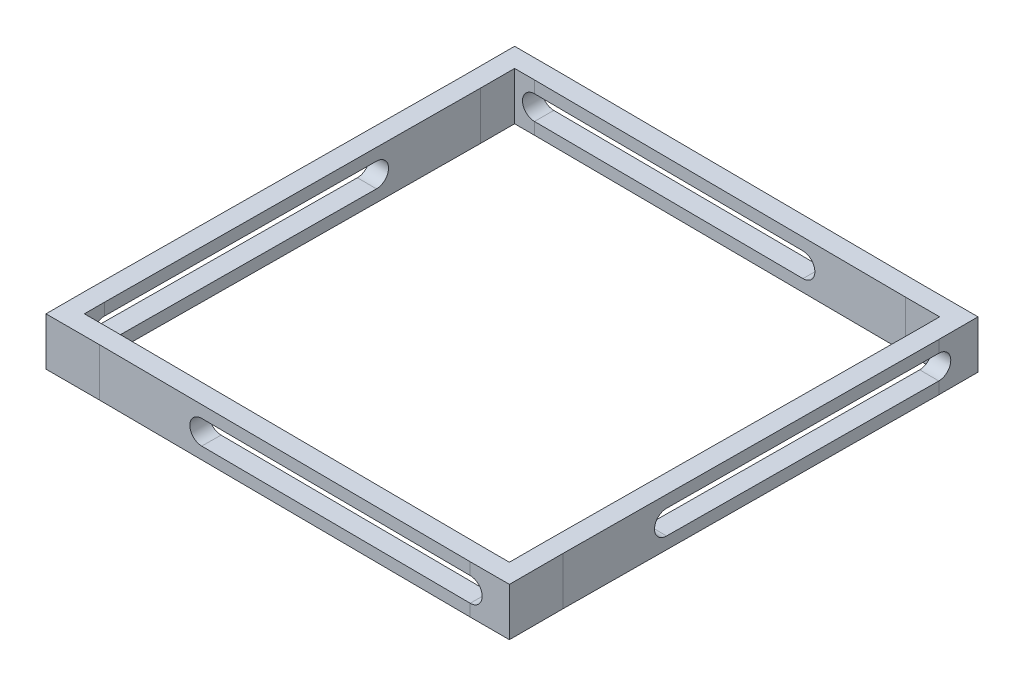
SolidWorks part; units mm, degrees
ref_plane "Front Plane" through (0, 0, 0) normal (0, 0, 1) x (1, 0, 0)
ref_plane "Top Plane" through (0, 0, 0) normal (0, 1, 0) x (1, 0, 0)
ref_plane "Right Plane" through (0, 0, 0) normal (1, 0, 0) x (0, 0, -1)
sketch "Sketch1" plane through (0, 0, 0) normal (0, 1, 0) x (1, 0, 0)
  line L1 (-48.1979, 37.1093) -> (-48.7381, -40.7678)
  line L3 (-37.6078, -48.9457) -> (40.2693, -49.4859)
  line L5 (48.4472, -38.3556) -> (48.9874, 39.5215)
  line L7 (37.8571, 47.6993) -> (-40.02, 48.2396)
  line L8 (-40.02, 48.2396) -> (-48.1979, 48.2396)
  line L9 (-48.1979, 48.2396) -> (-48.1979, 37.1093)
  line L10 (37.8571, 47.6993) -> (48.9874, 47.6993)
  line L11 (48.9874, 47.6993) -> (48.9874, 39.5215)
  line L12 (40.2693, -49.4859) -> (48.4472, -49.4859)
  line L13 (48.4472, -49.4859) -> (48.4472, -38.3556)
  line L14 (-37.6078, -48.9457) -> (-48.7381, -48.9457)
  line L15 (-48.7381, -48.9457) -> (-48.7381, -40.7678)
  line L16 (-40.0339, 44.2396) -> (-44.1979, 44.2396)
  line L17 (-44.1979, 44.2396) -> (-44.1979, 37.0954)
  line L18 (-44.1979, 37.0954) -> (-44.7381, -40.7817)
  line L19 (-44.7381, -44.9457) -> (-44.7381, -40.7817)
  line L20 (-37.5939, -44.9457) -> (-44.7381, -44.9457)
  line L21 (-37.5939, -44.9457) -> (40.2832, -45.4859)
  line L22 (40.2832, -45.4859) -> (44.4472, -45.4859)
  line L23 (44.4472, -45.4859) -> (44.4472, -38.3418)
  line L24 (44.4472, -38.3418) -> (44.9874, 39.5353)
  line L25 (44.9874, 43.6993) -> (44.9874, 39.5353)
  line L26 (37.8432, 43.6993) -> (44.9874, 43.6993)
  line L27 (37.8432, 43.6993) -> (-40.0339, 44.2396)
  dimension "D1" = 4
extrude "Boss-Extrude1" add sketch "Sketch1" along normal blind 10
sketch "Sketch2" plane through (0.3327, 0, -47.9596) normal (0.0069, 0, -1) x (-1, 0, -0.0069)
  line L0 (40.3537, 10) -> (40.3537, 0) construction
  circle A0 centre (40.3537, 5) radius 2.5
extrude "Cut-Extrude1" cut sketch "Sketch2" against normal blind 10
sketch "Sketch5" plane through (0, 10, 0) normal (0, 1, 0) x (1, 0, 0)
  line L0 (-44.1979, 44.2396) -> (44.4472, -45.4859) construction
  line L1 (-44.7381, -44.9457) -> (44.9874, 43.6993) construction
  point P8 (0.1246, -0.6232)
sketch3d "3DSketch1"
  line L0 (0.1246, 10, 0.6232) -> (0.1246, 5.2421, 0.6232) construction
  line L1 (-44.1979, 10, -44.2396) -> (44.4472, 10, 45.4859) construction
pattern_circular "CirPattern2" count 4 over 360 about axis through (0.1246, 10, 0.6232) along (0, -1, 0) of "Cut-Extrude1"
sketch "Sketch6" plane through (-0.3413, 0, 49.2042) normal (-0.0069, 0, 1) x (1, 0, 0.0069)
  line L0 (40.6116, 7.5) -> (-15.7674, 7.5)
  line L2 (40.6116, 2.5) -> (-15.7674, 2.5)
  line L3 (-18.2674, 5) -> (40.6116, 5) construction
  arc A0 (40.6116, 2.5) -> (40.6116, 7.5) centre (40.6116, 5) ccw
  arc A2 (-15.7674, 7.5) -> (-15.7674, 2.5) centre (-15.7674, 5) ccw
extrude "Cut-Extrude2" cut sketch "Sketch6" against normal blind 5 and the other way blind 1
pattern_circular "CirPattern3" count 4 over 360 about axis through (0.1246, 10, 0.6232) along (0, -1, 0) of "Cut-Extrude2"
